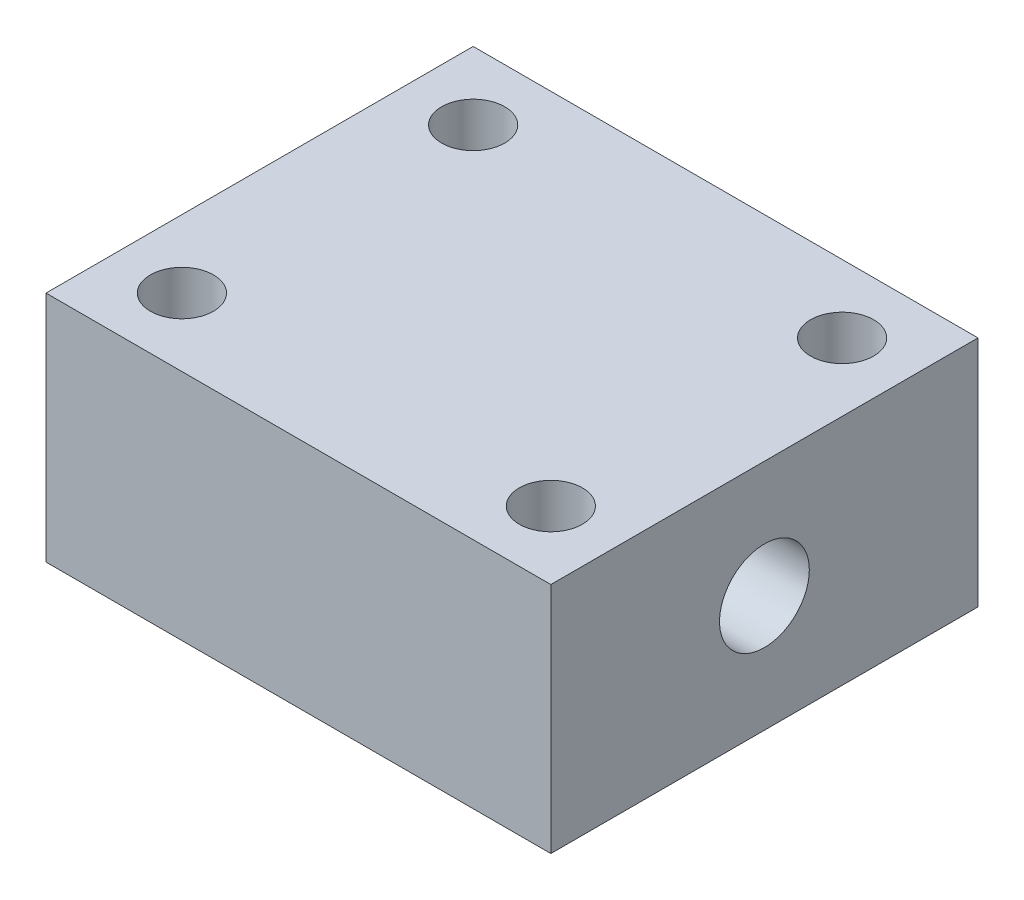
SolidWorks part; units mm, degrees
ref_plane "Front Plane" through (0, 0, 0) normal (0, 0, 1) x (1, 0, 0)
ref_plane "Top Plane" through (0, 0, 0) normal (0, 1, 0) x (1, 0, 0)
ref_plane "Right Plane" through (0, 0, 0) normal (1, 0, 0) x (0, 0, -1)
sketch "Sketch1" plane through (0, 0, 0) normal (0, 1, 0) x (1, 0, 0)
  line L1 (-41.275, -34.925) -> (41.275, -34.925)
  line L2 (-41.275, -34.925) -> (-41.275, 34.925)
  line L3 (-41.275, 34.925) -> (41.275, 34.925)
  line L4 (41.275, -34.925) -> (41.275, 34.925)
  line L5 (-41.275, -34.925) -> (41.275, 34.925) construction
  line L6 (-41.275, 34.925) -> (41.275, -34.925) construction
  point P0 (0, 0)
  dimension "D1" = 41.275
  dimension "D2" = 34.925
extrude "Boss-Extrude1" add sketch "Sketch1" along normal mid plane 38.1
sketch "Sketch2" plane through (0, 0, 0) normal (0, 1, 0) x (1, 0, 0)
  circle A0 centre (-30.1625, -23.8125) radius 5.1594
  circle A1 centre (30.1625, -23.8125) radius 5.1594
  circle A2 centre (-30.1625, 23.8125) radius 5.1594
  circle A3 centre (30.1625, 23.8125) radius 5.1594
  point P8 (0, 0)
  dimension "D1" = 10.3188
  dimension "D2" = 10.3187
  dimension "D3" = 10.3187
  dimension "D4" = 10.3188
  dimension "D5" = 60.325
  dimension "D6" = 47.625
  dimension "D7" = 30.1625
  dimension "D8" = 23.8125
extrude "Cut-Extrude2" cut sketch "Sketch2" along normal through all from offset 19.05
sketch "Sketch3" plane through (0, 0, 0) normal (0, 1, 0) x (1, 0, 0)
  circle A0 centre (-17.4625, 0) radius 7.3422
  circle A1 centre (17.4625, 0) radius 7.3422
  point P4 (0, 0)
  dimension "D1" = 14.6844
  dimension "D2" = 14.6844
  dimension "D3" = 34.925
  dimension "D4" = 17.4625
extrude "Cut-Extrude4" cut sketch "Sketch3" along normal blind 28.575 from offset 19.05
sketch "Sketch4" plane through (0, 0, 0) normal (0, 1, 0) x (1, 0, 0)
  circle A0 centre (-17.4625, 0) radius 12.7254
  circle A1 centre (17.4625, 0) radius 12.7254
  point P4 (0, 0)
  dimension "D1" = 25.4508
  dimension "D2" = 25.4508
  dimension "D3" = 34.925
  dimension "D4" = 17.4625
extrude "Cut-Extrude6" cut sketch "Sketch4" along normal blind 2.8194 from offset 19.05
sketch "Sketch5" plane through (0, 0, 0) normal (1, 0, 0) x (0, 0, -1)
  circle A0 centre (0, 0) radius 7.3422
  point P2 (0, 0)
  dimension "D1" = 14.6844
extrude "Cut-Extrude8" cut sketch "Sketch5" against normal blind 60.325 from offset 41.275
